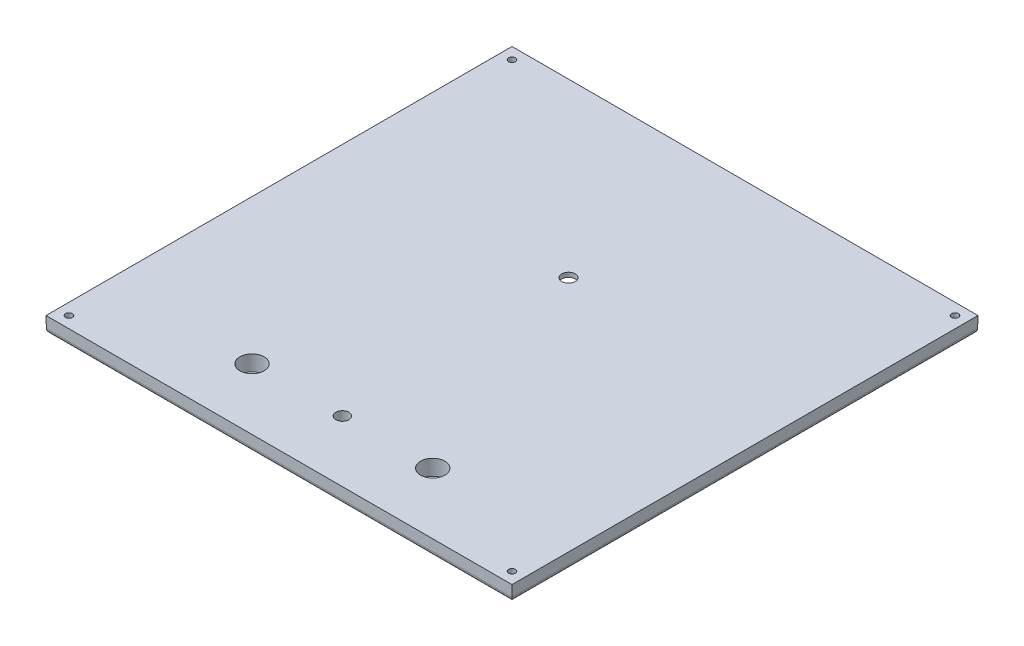
SolidWorks part; units mm, degrees
ref_plane "Front Plane" through (0, 0, 0) normal (0, 0, 1) x (1, 0, 0)
ref_plane "Top Plane" through (0, 0, 0) normal (0, 1, 0) x (1, 0, 0)
ref_plane "Right Plane" through (0, 0, 0) normal (1, 0, 0) x (0, 0, -1)
sketch "Sketch1" plane through (0, 0, 0) normal (0, 1, 0) x (1, 0, 0)
  line L1 (-103, 103) -> (103, 103)
  line L2 (-103, 103) -> (-103, -103)
  line L3 (-103, -103) -> (103, -103)
  line L4 (103, 103) -> (103, -103)
  line L5 (0, -103) -> (0, 103) construction
  line L6 (-103, 0) -> (103, 0) construction
  point P0 (0, 0)
  dimension "D1" = 206
  dimension "D2" = 206
extrude "MainBoss" add sketch "Sketch1" along normal blind 7 draft 1 contours L2 L3 L4 L1 draft outward yes
sketch "Sketch4" plane through (0, 0, 0) normal (0, -1, 0) x (-1, 0, 0)
  line L0 (-103, 103) -> (-103, -103) construction
  line L1 (103, -103) -> (-103, -103) construction
  circle A0 centre (2, 27) radius 70
  dimension "D1" = 140
  dimension "D2" = 105
  dimension "D3" = 130
extrude "TrayCut" cut sketch "Sketch4" against normal blind 5 draft 1 contours A0
sketch "Sketch5" plane through (0, 5, 0) normal (0, -1, 0) x (1, 0, 0)
  circle A0 centre (-2, -27) radius 3
  dimension "D1" = 6
extrude "TrayHole" cut sketch "Sketch5" against normal blind 7 draft 1
fillet "MainFillet" radius 2 5 edges at (-103, 0, 0) (0, 0, 103) (103, 0, 0) (0, 0, -103) (-2, 0, -97)
sketch "Sketch6" plane through (0, 0, 0) normal (0, -1, 0) x (1, 0, 0)
  line L0 (101.0346, 101.0346) -> (-101.0346, 101.0346) construction
  line L1 (-101.0346, 101.0346) -> (-101.0346, -101.0346) construction
  circle A0 centre (0.9654, 76.0533) radius 3
  circle A1 centre (-39.0346, 76.0346) radius 5.5
  circle A2 centre (40.9654, 76.0533) radius 5.5
  point P4 (0, 101.0346)
  dimension "D1" = 6
  dimension "D4" = 11
  dimension "D7" = 40
  dimension "D8" = 11
  dimension "D2" = 25
  dimension "D3" = 102
  dimension "D5" = 40
  dimension "D6" = 25
extrude "ShaftHoles" cut sketch "Sketch6" against normal blind 7 draft 1
sketch "Sketch7" plane through (0, 0, 0) normal (0, -1, 0) x (-1, 0, 0)
  line L0 (101.0346, -101.0346) -> (101.0346, 101.0346) construction
  line L1 (-101.0346, -101.0346) -> (101.0346, -101.0346) construction
  circle A0 centre (98.0346, -98.0346) radius 1.5
  dimension "D1" = 3
  dimension "D2" = 3
  dimension "D3" = 3
extrude "BackLeftHolder" cut sketch "Sketch7" against normal blind 7
sketch "Sketch8" plane through (0, 0, 0) normal (0, -1, 0) x (-1, 0, 0)
  line L0 (-101.0346, 101.0346) -> (-101.0346, -101.0346) construction
  line L1 (-101.0346, -101.0346) -> (101.0346, -101.0346) construction
  circle A0 centre (-98.0346, -98.0346) radius 1.5
  dimension "D1" = 3
  dimension "D2" = 3
  dimension "D3" = 3
extrude "BackRightHolder" cut sketch "Sketch8" against normal blind 7
sketch "Sketch9" plane through (0, 0, 0) normal (0, -1, 0) x (-1, 0, 0)
  line L0 (-101.0346, 101.0346) -> (-101.0346, -101.0346) construction
  line L1 (101.0346, 101.0346) -> (-101.0346, 101.0346) construction
  circle A0 centre (-98.0346, 98.0346) radius 1.5
  dimension "D1" = 3
  dimension "D2" = 3
  dimension "D3" = 3
extrude "FrontRightHolder" cut sketch "Sketch9" against normal blind 7
sketch "Sketch10" plane through (0, 0, 0) normal (0, -1, 0) x (-1, 0, 0)
  line L0 (101.0346, 101.0346) -> (-101.0346, 101.0346) construction
  line L1 (101.0346, -101.0346) -> (101.0346, 101.0346) construction
  circle A0 centre (98.0346, 98.0346) radius 1.5
  dimension "D1" = 3
  dimension "D2" = 3
  dimension "D3" = 3
extrude "FrontLeftHolder" cut sketch "Sketch10" against normal blind 7
